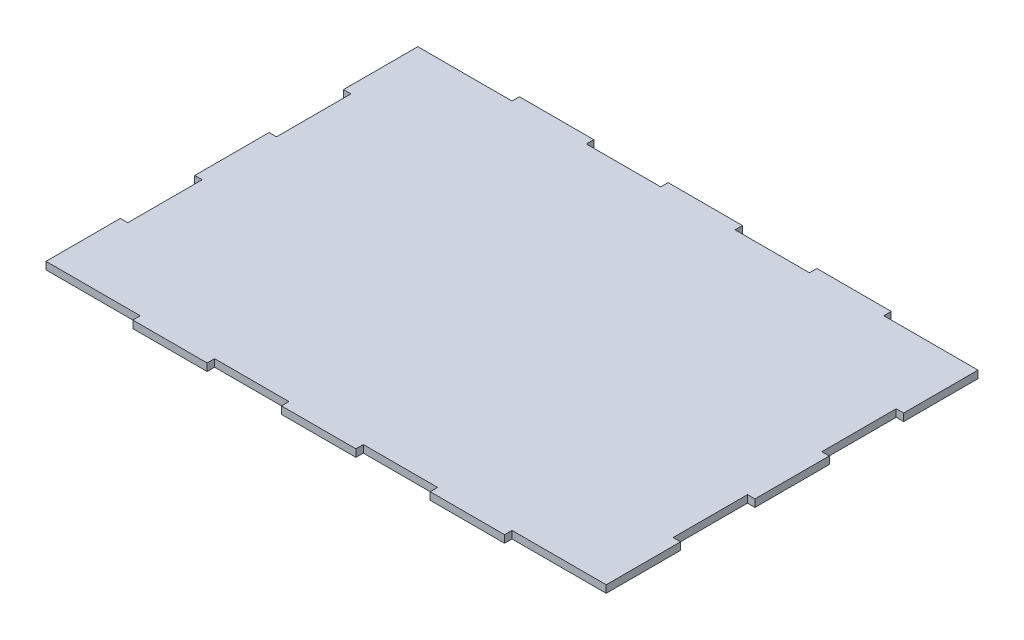
SolidWorks part; units mm, degrees
ref_plane "Front Plane" through (0, 0, 0) normal (0, 0, 1) x (1, 0, 0)
ref_plane "Top Plane" through (0, 0, 0) normal (0, 1, 0) x (1, 0, 0)
ref_plane "Right Plane" through (0, 0, 0) normal (1, 0, 0) x (0, 0, -1)
sketch "Sketch1" plane through (0, 0, 0) normal (0, 1, 0) x (1, 0, 0)
  line L1 (0, 0) -> (220, 0)
  line L2 (0, 0) -> (0, 150)
  line L3 (0, 150) -> (220, 150)
  line L4 (220, 0) -> (220, 150)
  line L8 (0, 75) -> (-6, 75) construction
  line L9 (-3, 60) -> (0, 60)
  line L10 (-3, 60) -> (-3, 90)
  line L11 (-3, 90) -> (0, 90)
  line L13 (-3, 60) -> (0, 75) construction
  line L14 (-3, 90) -> (0, 75) construction
  line L15 (-3, 120) -> (0, 120)
  line L16 (-3, 120) -> (-3, 150)
  line L17 (-3, 120) -> (0, 135) construction
  line L18 (-3, 150) -> (0, 135) construction
  line L19 (-3, 150) -> (0, 150)
  line L20 (-3, 0) -> (0, 0)
  line L21 (-3, 0) -> (-3, 30)
  line L22 (-3, 0) -> (0, 15) construction
  line L23 (-3, 30) -> (0, 15) construction
  line L24 (-3, 30) -> (0, 30)
  line L25 (110, 150) -> (110, 0) construction
  line L26 (223, 30) -> (220, 15) construction
  line L27 (223, 0) -> (220, 15) construction
  line L28 (223, 150) -> (220, 135) construction
  line L29 (223, 120) -> (220, 135) construction
  line L30 (223, 90) -> (220, 75) construction
  line L31 (223, 60) -> (220, 75) construction
  line L32 (220, 75) -> (226, 75) construction
  line L33 (223, 30) -> (220, 30)
  line L34 (223, 0) -> (223, 30)
  line L35 (223, 0) -> (220, 0)
  line L36 (223, 150) -> (220, 150)
  line L37 (223, 120) -> (223, 150)
  line L38 (223, 120) -> (220, 120)
  line L39 (223, 90) -> (220, 90)
  line L40 (223, 60) -> (223, 90)
  line L41 (223, 60) -> (220, 60)
  line L42 (220, 0) -> (220, 150)
  line L43 (95, -3) -> (125, 0) construction
  line L44 (125, 0) -> (95, 0)
  line L45 (125, 0) -> (125, -3)
  line L46 (125, -3) -> (95, -3)
  line L47 (95, 0) -> (95, -3)
  line L48 (125, -3) -> (95, 0) construction
  line L49 (110, -1.5) -> (110, 0) construction
  line L50 (185, 0) -> (185, -3)
  line L51 (185, 0) -> (155, 0)
  line L52 (155, 0) -> (155, -3)
  line L53 (185, -3) -> (155, -3)
  line L54 (65, 0) -> (65, -3)
  line L55 (65, 0) -> (35, 0)
  line L56 (35, 0) -> (35, -3)
  line L57 (65, -3) -> (35, -3)
  line L58 (220, 75) -> (0, 75) construction
  line L59 (110, 151.5) -> (110, 150) construction
  line L60 (125, 153) -> (95, 150) construction
  line L61 (95, 153) -> (125, 150) construction
  line L62 (65, 153) -> (35, 153)
  line L63 (35, 150) -> (35, 153)
  line L64 (65, 150) -> (35, 150)
  line L65 (65, 150) -> (65, 153)
  line L66 (185, 153) -> (155, 153)
  line L67 (155, 150) -> (155, 153)
  line L68 (185, 150) -> (155, 150)
  line L69 (185, 150) -> (185, 153)
  line L70 (95, 150) -> (95, 153)
  line L71 (125, 153) -> (95, 153)
  line L72 (125, 150) -> (125, 153)
  line L73 (125, 150) -> (95, 150)
  point P6 (0, 75)
  point P12 (-3, 75)
  point P39 (220, 75)
  point P55 (110, 75)
  dimension "D1" = 220
  dimension "D2" = 150
  dimension "D3" = 30
  dimension "D4" = 3
  dimension "D7" = 3
  dimension "D8" = 30
  dimension "D5" = 2
  dimension "D6" = 2
  dimension "D9" = 2
  dimension "D10" = 2
extrude "Boss-Extrude1" add sketch "Sketch1" along normal blind 3 contours L1 L4 L3 L2 | L24 L21 L20 L2 | L11 L10 L9 L2 | L19 L16 L15 L2 | L3 L65 L62 L63 | L3 L72 L71 L70 | L3 L69 L66 L67 | L38 L37 L36 L4 | L41 L40 L39 L4 | L35 L34 L33 L4 | L53 L50 L1 L52 | L1 L47 L46 L45 | L57 L54 L1 L56
